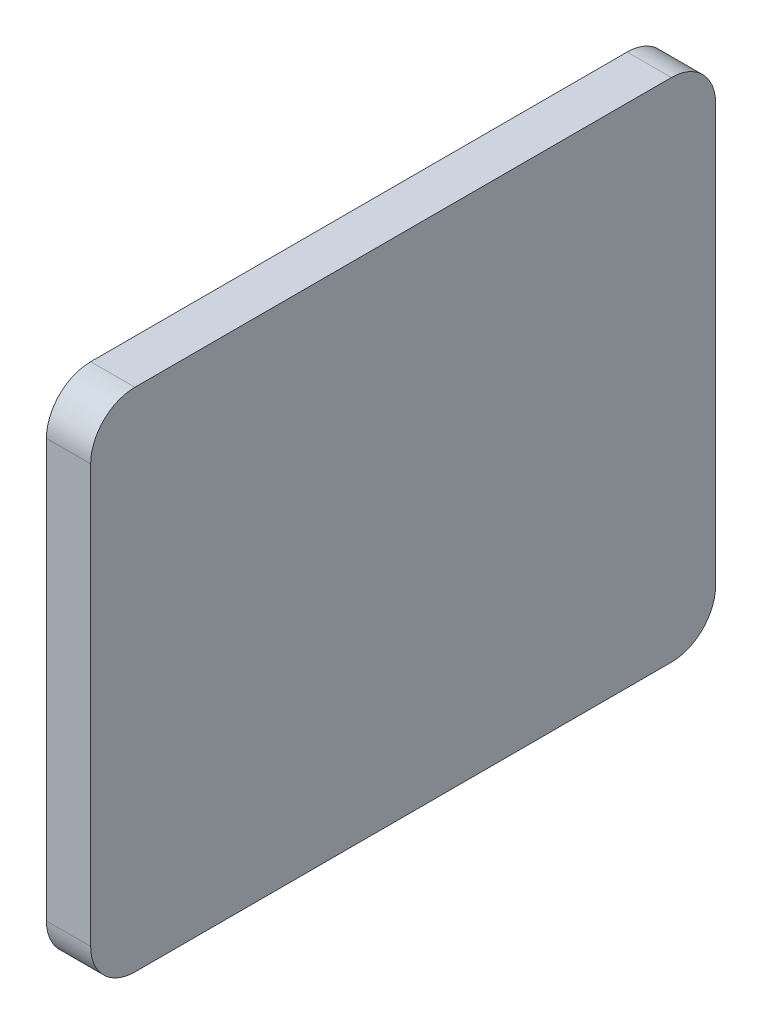
SolidWorks part; units mm, degrees
ref_plane "Front Plane" through (0, 0, 0) normal (0, 0, 1) x (1, 0, 0)
ref_plane "Top Plane" through (0, 0, 0) normal (0, 1, 0) x (1, 0, 0)
ref_plane "Right Plane" through (0, 0, 0) normal (1, 0, 0) x (0, 0, -1)
sketch "Sketch1" plane through (0, 0, 0) normal (1, 0, 0) x (0, 0, -1)
  line L1 (10, 0) -> (131.2922, 0)
  line L2 (0, -10) -> (0, -104.4885)
  line L3 (10, -114.4885) -> (131.2922, -114.4885)
  line L4 (141.2922, -10) -> (141.2922, -104.4885)
  arc A0 (131.2922, -114.4885) -> (141.2922, -104.4885) centre (131.2922, -104.4885) ccw
  arc A1 (10, -114.4885) -> (0, -104.4885) centre (10, -104.4885) cw
  arc A2 (10, 0) -> (0, -10) centre (10, -10) ccw
  arc A3 (131.2922, 0) -> (141.2922, -10) centre (131.2922, -10) cw
  dimension "D1" = 10
extrude "Boss-Extrude1" add sketch "Sketch1" along normal blind 10
sketch "Sketch2" plane through (0, 0, 0) normal (-1, 0, 0) x (0, 0, 1)
  line L1 (-136.0175, -87.5845) -> (-9.7778, -87.5845)
  line L2 (-136.0175, -87.5845) -> (-136.0175, -111.4358)
  line L3 (-136.0175, -111.4358) -> (-9.7778, -111.4358)
  line L4 (-9.7778, -87.5845) -> (-9.7778, -111.4358)
extrude "Boss-Extrude2" add sketch "Sketch2" along normal blind 1
sketch "Sketch3" plane through (0, 0, 0) normal (-1, 0, 0) x (0, 0, 1)
  line L1 (-95.1413, -8.4587) -> (-8.5205, -8.4587)
  line L2 (-95.1413, -8.4587) -> (-95.1413, -48.9396)
  line L3 (-95.1413, -48.9396) -> (-8.5205, -48.9396)
  line L4 (-8.5205, -8.4587) -> (-8.5205, -48.9396)
extrude "Cut-Extrude1" cut sketch "Sketch3" against normal blind 1
sketch "Sketch4" plane through (0, 0, 0) normal (-1, 0, 0) x (0, 0, 1)
  line L0 (-132.2131, -20.3589) -> (-128.7909, -24.9156)
  line L1 (-130.3672, -18.5747) -> (-126.8497, -22.8146)
  line L2 (-111.9319, -17.5151) -> (-115.0498, -22.1795)
  line L3 (-113.3237, -23.5919) -> (-110.5158, -18.6927)
  line L4 (-127.5897, -37.7547) -> (-130.5551, -42.5028)
  line L5 (-112.7792, -37.0375) -> (-109.3332, -41.4401)
  line L6 (-126.2203, -38.8907) -> (-129.2823, -43.4715)
  line L7 (-114.0146, -38.2855) -> (-110.5158, -42.5028)
  line L8 (-110.5158, -42.5028) -> (-110.4969, -42.5252)
  arc A0 (-132.2131, -20.3589) -> (-130.5551, -42.5028) centre (-120.5127, -30.6169) ccw
  arc A1 (-128.7909, -24.9156) -> (-127.5897, -37.7547) centre (-120.5127, -30.6169) ccw
  arc A2 (-115.0498, -22.1795) -> (-126.8497, -22.8146) centre (-120.5127, -30.6169) ccw
  arc A3 (-111.9882, -17.5993) -> (-130.3672, -18.5747) centre (-120.5127, -30.6169) ccw
  arc A4 (-126.2203, -38.8907) -> (-114.0146, -38.2855) centre (-120.5127, -30.6169) ccw
  arc A5 (-129.2819, -43.4709) -> (-110.4969, -42.5252) centre (-120.5127, -30.6169) ccw
  arc A6 (-112.7792, -37.0375) -> (-113.3237, -23.5919) centre (-120.5127, -30.6169) ccw
  arc A7 (-109.3332, -41.4401) -> (-110.5158, -18.6927) centre (-120.5127, -30.6169) ccw
  point P2 (-127.4859, -37.5886)
  point P11 (-112.7792, -37.0375)
extrude "Boss-Extrude3" add sketch "Sketch4" along normal blind 1 contours A1 L0 A0 L4 | L2 A3 L1 A2 | L5 A7 L3 A6 | L6 A5 L8 L7 A4
sketch "Sketch5" plane through (-1, 0, 0) normal (-1, 0, 0) x (0, 0, 1)
  line L0 (-122.6573, -19.3449) -> (-119.2891, -19.3449)
  line L1 (-119.2891, -19.3449) -> (-120.9732, -16.1746)
  line L2 (-120.9732, -16.1746) -> (-122.6573, -19.3449)
extrude "Cut-Extrude2" cut sketch "Sketch5" against normal blind 1
sketch "Sketch6" plane through (-1, 0, 0) normal (-1, 0, 0) x (0, 0, 1)
  line L0 (-132.0461, -29.687) -> (-132.0461, -33.1027)
  line L1 (-132.0461, -33.1027) -> (-135.4492, -31.3949)
  line L2 (-135.4492, -31.3949) -> (-132.0461, -29.687)
  line L3 (-122.5724, -41.7347) -> (-118.4594, -41.7347)
  line L4 (-118.4594, -41.7347) -> (-120.5159, -44.7663)
  line L5 (-120.5159, -44.7663) -> (-122.5724, -41.7347)
  line L6 (-109.6773, -28.718) -> (-109.6773, -32.698)
  line L7 (-109.6773, -32.698) -> (-106.1102, -30.2783)
  line L8 (-106.1102, -30.2783) -> (-109.6773, -28.718)
extrude "Cut-Extrude3" cut sketch "Sketch6" against normal blind 1
sketch "Sketch7" plane through (0, 0, 0) normal (-1, 0, 0) x (0, 0, 1)
  circle A0 centre (-120.7611, -31.1405) radius 5.8184
  point P2 (-120.7611, -31.1405)
extrude "Boss-Extrude4" add sketch "Sketch7" along normal blind 1
sketch "Sketch8" plane through (-1, 0, 0) normal (-1, 0, 0) x (0, 0, 1)
  line L0 (-121.1763, -28.9978) -> (-120.4435, -28.9978)
  line L1 (-120.4435, -28.9978) -> (-120.4435, -33.4647)
  line L2 (-121.1763, -28.9978) -> (-121.1744, -33.4887)
  line L3 (-121.924, -30.2154) -> (-121.682, -30.8856)
  line L4 (-119.7858, -30.2154) -> (-119.9704, -30.9276)
  arc A0 (-121.924, -30.2154) -> (-119.7858, -30.2154) centre (-120.8549, -32.0753) ccw
  arc A1 (-121.682, -30.8856) -> (-121.1744, -33.4887) centre (-120.8549, -32.0753) ccw
  arc A2 (-120.4435, -33.4647) -> (-119.9704, -30.9276) centre (-120.8549, -32.0753) ccw
  point P1 (-121.3518, -33.4365)
extrude "Cut-Extrude4" cut sketch "Sketch8" against normal blind 1
sketch "Sketch9" plane through (1, 0, 0) normal (-1, 0, 0) x (0, 0, 1)
  line L1 (-93.278, -10.5043) -> (-10.3118, -10.5043)
  line L2 (-93.278, -10.5043) -> (-93.278, -47.1944)
  line L3 (-93.278, -47.1944) -> (-10.3118, -47.1944)
  line L4 (-10.3118, -10.5043) -> (-10.3118, -47.1944)
extrude "Boss-Extrude5" add sketch "Sketch9" along normal blind 1
sketch "Sketch10" plane through (0, 0, 0) normal (-1, 0, 0) x (0, 0, 1)
  circle A0 centre (-85.8196, -69.1459) radius 6.4003
  circle A1 centre (-60.8719, -69.1459) radius 6.2565
  circle A2 centre (-37.8784, -69.1459) radius 5.7929
  point P4 (-37.8784, -69.1459)
extrude "Boss-Extrude6" add sketch "Sketch10" along normal blind 1
sketch "Sketch11" plane through (0, 0, 0) normal (-1, 0, 0) x (0, 0, 1)
  line L0 (-124.9995, -56.7638) -> (-122.0267, -56.7638)
  line L1 (-132.2152, -55.2914) -> (-98.6974, -55.2914)
  line L2 (-132.2152, -55.2914) -> (-132.2152, -84.0286)
  line L3 (-132.2152, -84.0286) -> (-98.6974, -84.0286)
  line L4 (-98.6974, -55.2914) -> (-98.6974, -84.0286)
  line L5 (-130.6033, -56.6632) -> (-127.6305, -56.6632)
  line L6 (-130.6033, -56.6632) -> (-130.6033, -58.7612)
  line L7 (-130.6033, -58.7612) -> (-127.6305, -58.7612)
  line L8 (-127.6305, -56.6632) -> (-127.6305, -58.7612)
  line L9 (-124.9995, -56.7638) -> (-124.9995, -58.8618)
  line L10 (-124.9995, -58.8618) -> (-122.0267, -58.8618)
  line L11 (-122.0267, -56.7638) -> (-122.0267, -58.8618)
  line L12 (-1.4864, -56.7638) -> (1.4864, -56.7638)
  line L13 (-1.4864, -56.7638) -> (-1.4864, -58.8618)
  line L14 (-1.4864, -58.8618) -> (1.4864, -58.8618)
  line L15 (1.4864, -56.7638) -> (1.4864, -58.8618)
  line L16 (-1.4864, -56.7638) -> (1.4864, -56.7638)
  line L17 (-1.4864, -56.7638) -> (-1.4864, -58.8618)
  line L18 (-1.4864, -58.8618) -> (1.4864, -58.8618)
  line L19 (1.4864, -56.7638) -> (1.4864, -58.8618)
  line L21 (-119.5759, -56.7638) -> (-116.4441, -56.7638)
  line L22 (-119.5759, -56.7638) -> (-119.5759, -58.8859)
  line L23 (-119.5759, -58.8859) -> (-116.4441, -58.8859)
  line L24 (-116.4441, -56.7638) -> (-116.4441, -58.8859)
  line L25 (-114.2123, -56.7638) -> (-111.2408, -56.7638)
  line L26 (-114.2123, -56.7638) -> (-114.2123, -59.0052)
  line L27 (-114.2123, -59.0052) -> (-111.2408, -59.0052)
  line L28 (-111.2408, -56.7638) -> (-111.2408, -59.0052)
  line L29 (-108.5727, -56.7638) -> (-105.7946, -56.7638)
  line L30 (-108.5727, -56.7638) -> (-108.5727, -59.0052)
  line L31 (-108.5727, -59.0052) -> (-105.7946, -59.0052)
  line L32 (-105.7946, -56.7638) -> (-105.7946, -59.0052)
  line L33 (-103.3284, -56.7638) -> (-100.4528, -56.7638)
  line L34 (-103.3284, -56.7638) -> (-103.3284, -59.0052)
  line L35 (-103.3284, -59.0052) -> (-100.4528, -59.0052)
  line L36 (-100.4528, -56.7638) -> (-100.4528, -59.0052)
  line L37 (-130.7125, -60.9213) -> (-127.6305, -60.9213)
  line L38 (-130.7125, -60.9213) -> (-130.7125, -63.1632)
  line L39 (-130.7125, -63.1632) -> (-127.6305, -63.1632)
  line L40 (-127.6305, -60.9213) -> (-127.6305, -63.1632)
  line L41 (-130.7125, -65.4686) -> (-127.6305, -65.4686)
  line L42 (-130.7125, -65.4686) -> (-130.7125, -67.9428)
  line L43 (-130.7125, -67.9428) -> (-127.6305, -67.9428)
  line L44 (-127.6305, -65.4686) -> (-127.6305, -67.9428)
  line L45 (-130.7125, -70.4302) -> (-127.6305, -70.4302)
  line L46 (-130.7125, -70.4302) -> (-130.7125, -72.9487)
  line L47 (-130.7125, -72.9487) -> (-127.6305, -72.9487)
  line L48 (-127.6305, -70.4302) -> (-127.6305, -72.9487)
  line L49 (-130.7125, -75.6103) -> (-127.6305, -75.6103)
  line L50 (-130.7125, -75.6103) -> (-130.7125, -77.9537)
  line L51 (-130.7125, -77.9537) -> (-127.6305, -77.9537)
  line L52 (-127.6305, -75.6103) -> (-127.6305, -77.9537)
  line L53 (-130.7125, -79.3964) -> (-127.6305, -79.3964)
  line L54 (-130.7125, -79.3964) -> (-130.7125, -81.9145)
  line L55 (-130.7125, -81.9145) -> (-127.6305, -81.9145)
  line L56 (-127.6305, -79.3964) -> (-127.6305, -81.9145)
  line L57 (-124.9995, -60.9213) -> (-122.0267, -60.9213)
  line L58 (-124.9995, -60.9213) -> (-124.9995, -63.1632)
  line L59 (-124.9995, -63.1632) -> (-122.0267, -63.1632)
  line L60 (-122.0267, -60.9213) -> (-122.0267, -63.1632)
  line L61 (-124.9995, -65.4686) -> (-122.0267, -65.4686)
  line L62 (-124.9995, -65.4686) -> (-124.9995, -67.9428)
  line L63 (-124.9995, -67.9428) -> (-122.0267, -67.9428)
  line L64 (-122.0267, -65.4686) -> (-122.0267, -67.9428)
  line L65 (-124.9995, -70.4302) -> (-122.0267, -70.4302)
  line L66 (-124.9995, -70.4302) -> (-124.9995, -72.9487)
  line L67 (-124.9995, -72.9487) -> (-122.0267, -72.9487)
  line L68 (-122.0267, -70.4302) -> (-122.0267, -72.9487)
  line L69 (-124.9995, -75.6103) -> (-122.0267, -75.6103)
  line L70 (-124.9995, -75.6103) -> (-124.9995, -77.9537)
  line L71 (-124.9995, -77.9537) -> (-122.0267, -77.9537)
  line L72 (-122.0267, -75.6103) -> (-122.0267, -77.9537)
  line L73 (-124.9995, -79.3964) -> (-122.0267, -79.3964)
  line L74 (-124.9995, -79.3964) -> (-124.9995, -81.9145)
  line L75 (-124.9995, -81.9145) -> (-122.0267, -81.9145)
  line L76 (-122.0267, -79.3964) -> (-122.0267, -81.9145)
  line L77 (-119.5759, -60.9213) -> (-116.4441, -60.9213)
  line L78 (-119.5759, -60.9213) -> (-119.5759, -63.1632)
  line L79 (-119.5759, -63.1632) -> (-116.4441, -63.1632)
  line L80 (-116.4441, -60.9213) -> (-116.4441, -63.1632)
  line L81 (-114.2123, -60.9213) -> (-111.2408, -60.9213)
  line L82 (-114.2123, -60.9213) -> (-114.2123, -63.1632)
  line L83 (-114.2123, -63.1632) -> (-111.2408, -63.1632)
  line L84 (-111.2408, -60.9213) -> (-111.2408, -63.1632)
  line L85 (-108.5727, -60.9213) -> (-105.7946, -60.9213)
  line L86 (-108.5727, -60.9213) -> (-108.5727, -63.1632)
  line L87 (-108.5727, -63.1632) -> (-105.7946, -63.1632)
  line L88 (-105.7946, -60.9213) -> (-105.7946, -63.1632)
  line L89 (-103.3284, -60.9213) -> (-100.4528, -60.9213)
  line L90 (-103.3284, -60.9213) -> (-103.3284, -63.1632)
  line L91 (-103.3284, -63.1632) -> (-100.4528, -63.1632)
  line L92 (-100.4528, -60.9213) -> (-100.4528, -63.1632)
  line L93 (-119.5759, -65.4686) -> (-116.1815, -65.4686)
  line L94 (-119.5759, -65.4686) -> (-119.5759, -67.9428)
  line L95 (-119.5759, -67.9428) -> (-116.1815, -67.9428)
  line L96 (-116.1815, -65.4686) -> (-116.1815, -67.9428)
  line L97 (-114.2123, -65.4686) -> (-111.2408, -65.4686)
  line L98 (-114.2123, -65.4686) -> (-114.2123, -67.9428)
  line L99 (-114.2123, -67.9428) -> (-111.2408, -67.9428)
  line L100 (-111.2408, -65.4686) -> (-111.2408, -67.9428)
  line L101 (-108.5727, -65.4686) -> (-105.7946, -65.4686)
  line L102 (-108.5727, -65.4686) -> (-108.5727, -67.9428)
  line L103 (-108.5727, -67.9428) -> (-105.7946, -67.9428)
  line L104 (-105.7946, -65.4686) -> (-105.7946, -67.9428)
  line L105 (-103.3284, -65.4686) -> (-100.4528, -65.4686)
  line L106 (-103.3284, -65.4686) -> (-103.3284, -67.9428)
  line L107 (-103.3284, -67.9428) -> (-100.4528, -67.9428)
  line L108 (-100.4528, -65.4686) -> (-100.4528, -67.9428)
  line L109 (-119.5759, -70.4302) -> (-116.4441, -70.4302)
  line L110 (-119.5759, -70.4302) -> (-119.5759, -72.9487)
  line L111 (-119.5759, -72.9487) -> (-116.4441, -72.9487)
  line L112 (-116.4441, -70.4302) -> (-116.4441, -72.9487)
  line L113 (-114.2123, -70.4302) -> (-111.2408, -70.4302)
  line L114 (-114.2123, -70.4302) -> (-114.2123, -72.9487)
  line L115 (-114.2123, -72.9487) -> (-111.2408, -72.9487)
  line L116 (-111.2408, -70.4302) -> (-111.2408, -72.9487)
  line L117 (-108.5727, -70.4302) -> (-105.7946, -70.4302)
  line L118 (-108.5727, -70.4302) -> (-108.5727, -72.9487)
  line L119 (-108.5727, -72.9487) -> (-105.7946, -72.9487)
  line L120 (-105.7946, -70.4302) -> (-105.7946, -72.9487)
  line L121 (-103.3284, -70.4302) -> (-100.4528, -70.4302)
  line L122 (-103.3284, -70.4302) -> (-103.3284, -72.9487)
  line L123 (-103.3284, -72.9487) -> (-100.4528, -72.9487)
  line L124 (-100.4528, -70.4302) -> (-100.4528, -72.9487)
  line L125 (-119.5759, -75.6103) -> (-116.4441, -75.6103)
  line L126 (-119.5759, -75.6103) -> (-119.5759, -77.9537)
  line L127 (-119.5759, -77.9537) -> (-116.4441, -77.9537)
  line L128 (-116.4441, -75.6103) -> (-116.4441, -77.9537)
  line L129 (-114.2123, -75.4941) -> (-111.2408, -75.4941)
  line L130 (-114.2123, -75.4941) -> (-114.2123, -77.9537)
  line L131 (-114.2123, -77.9537) -> (-111.2408, -77.9537)
  line L132 (-111.2408, -75.4941) -> (-111.2408, -77.9537)
  line L133 (-108.5727, -75.4941) -> (-105.7946, -75.4941)
  line L134 (-108.5727, -75.4941) -> (-108.5727, -77.9537)
  line L135 (-108.5727, -77.9537) -> (-105.7946, -77.9537)
  line L136 (-105.7946, -75.4941) -> (-105.7946, -77.9537)
  line L137 (-103.3284, -75.4941) -> (-100.4528, -75.4941)
  line L138 (-103.3284, -75.4941) -> (-103.3284, -77.9537)
  line L139 (-103.3284, -77.9537) -> (-100.4528, -77.9537)
  line L140 (-100.4528, -75.4941) -> (-100.4528, -77.9537)
  line L141 (-119.5759, -79.3964) -> (-116.4441, -79.3964)
  line L142 (-119.5759, -79.3964) -> (-119.5759, -81.9145)
  line L143 (-119.5759, -81.9145) -> (-116.4441, -81.9145)
  line L144 (-116.4441, -79.3964) -> (-116.4441, -81.9145)
  line L145 (-114.2123, -79.3964) -> (-111.2408, -79.3964)
  line L146 (-114.2123, -79.3964) -> (-114.2123, -82.0606)
  line L147 (-114.2123, -82.0606) -> (-111.2408, -82.0606)
  line L148 (-111.2408, -79.3964) -> (-111.2408, -82.0606)
  line L149 (-108.5727, -79.3964) -> (-105.7946, -79.3964)
  line L150 (-108.5727, -79.3964) -> (-108.5727, -82.0606)
  line L151 (-108.5727, -82.0606) -> (-105.7946, -82.0606)
  line L152 (-105.7946, -79.3964) -> (-105.7946, -82.0606)
  line L153 (-103.3284, -79.3964) -> (-100.4528, -79.3964)
  line L154 (-103.3284, -79.3964) -> (-103.3284, -82.0606)
  line L155 (-103.3284, -82.0606) -> (-100.4528, -82.0606)
  line L156 (-100.4528, -79.3964) -> (-100.4528, -82.0606)
extrude "Boss-Extrude8" add sketch "Sketch11" along normal blind 1 contours L8 L5 L6 L7 | L40 L37 L38 L39 | L44 L41 L42 L43 | L48 L45 L46 L47 | L52 L49 L50 L51 | L76 L73 L74 L75 | L72 L69 L70 L71 | L68 L65 L66 L67 | L64 L61 L62 L63 | L60 L57 L58 L59 | L11 L0 L9 L10 | L24 L21 L22 L23 | L80 L77 L78 L79 | L96 L93 L94 L95 | L112 L109 L110 L111 | L128 L125 L126 L127 | L144 L141 L142 L143 | L148 L145 L146 L147 | L132 L129 L130 L131 | L116 L113 L114 L115 | L84 L81 L82 L83 | L28 L25 L26 L27 | L32 L29 L30 L31 | L88 L85 L86 L87 | L104 L101 L102 L103 | L120 L117 L118 L119 | L136 L133 L134 L135 | L152 L149 L150 L151 | L156 L153 L154 L155 | L140 L137 L138 L139 | L124 L121 L122 L123 | L108 L105 L106 L107 | L92 L89 L90 L91 | L36 L33 L34 L35 | L56 L55 L54 L53 | L97 L100 L99 L98
sketch "Sketch12" plane through (0, 0, 0) normal (-1, 0, 0) x (0, 0, 1)
  line L1 (-133.2407, -54.6964) -> (-97.6755, -54.6964)
  line L2 (-133.2407, -54.6964) -> (-133.2407, -84.366)
  line L3 (-133.2407, -84.366) -> (-97.6755, -84.366)
  line L4 (-97.6755, -54.6964) -> (-97.6755, -84.366)
  line L5 (-132.4303, -55.3589) -> (-98.6763, -55.3589)
  line L6 (-132.4303, -55.3589) -> (-132.4303, -83.6565)
  line L7 (-132.4303, -83.6565) -> (-98.6763, -83.6565)
  line L8 (-98.6763, -55.3589) -> (-98.6763, -83.6565)
extrude "Boss-Extrude9" add sketch "Sketch12" along normal blind 1
sketch "Sketch13" plane through (0, 0, 0) normal (-1, 0, 0) x (0, 0, 1)
  line L1 (-91.0194, -12.7672) -> (-80.505, -12.7672)
  line L2 (-91.0194, -12.7672) -> (-91.0194, -17.7701)
  line L3 (-91.0194, -17.7701) -> (-80.505, -17.7701)
  line L4 (-80.505, -12.7672) -> (-80.505, -17.7701)
  line L5 (-80.505, -14.2408) -> (-79.5475, -14.2408)
  line L6 (-80.505, -14.2408) -> (-80.505, -16.1953)
  line L7 (-80.505, -16.1953) -> (-79.5475, -16.1953)
  line L8 (-79.5475, -14.2408) -> (-79.5475, -16.1953)
extrude "Cut-Extrude5" cut sketch "Sketch13" against normal blind 1 contours L4 L1 L2 L3 | L8 L5 L4 L7
sketch "Sketch14" plane through (1, 0, 0) normal (-1, 0, 0) x (0, 0, 1)
  line L1 (-90.3761, -13.2499) -> (-88.5898, -13.2499)
  line L2 (-90.3761, -13.2499) -> (-90.3761, -17.3688)
  line L3 (-90.3761, -17.3688) -> (-88.5898, -17.3688)
  line L4 (-88.5898, -13.2499) -> (-88.5898, -17.3688)
  line L5 (-87.6464, -13.2499) -> (-85.9931, -13.2499)
  line L6 (-87.6464, -13.2499) -> (-87.6464, -17.3688)
  line L7 (-87.6464, -17.3688) -> (-85.9931, -17.3688)
  line L8 (-85.9931, -13.2499) -> (-85.9931, -17.3688)
  line L9 (-85.3146, -13.2499) -> (-83.7932, -13.2499)
  line L10 (-85.3146, -13.2499) -> (-85.3146, -17.3688)
  line L11 (-85.3146, -17.3688) -> (-83.7932, -17.3688)
  line L12 (-83.7932, -13.2499) -> (-83.7932, -17.3688)
  line L13 (-82.8766, -13.2499) -> (-81.4087, -13.2499)
  line L14 (-82.8766, -13.2499) -> (-82.8766, -17.3688)
  line L15 (-82.8766, -17.3688) -> (-81.4087, -17.3688)
  line L16 (-81.4087, -13.2499) -> (-81.4087, -17.3688)
extrude "Boss-Extrude10" add sketch "Sketch14" along normal blind 1
sketch "Sketch15" plane through (0, 0, 0) normal (-1, 0, 0) x (0, 0, 1)
  line L1 (-76.0669, -12.5916) -> (-74.4007, -12.5916)
  line L2 (-76.0669, -12.5916) -> (-76.0669, -18.1366)
  line L3 (-76.0669, -18.1366) -> (-74.4007, -18.1366)
  line L4 (-74.4007, -12.5916) -> (-74.4007, -18.1366)
  line L5 (-73.4129, -13.583) -> (-71.9662, -13.583)
  line L6 (-73.4129, -13.583) -> (-73.4129, -18.1366)
  line L7 (-73.4129, -18.1366) -> (-71.9662, -18.1366)
  line L8 (-71.9662, -13.583) -> (-71.9662, -18.1366)
  line L9 (-70.6716, -14.7042) -> (-69.3584, -14.7042)
  line L10 (-70.6716, -14.7042) -> (-70.6716, -18.1366)
  line L11 (-70.6716, -18.1366) -> (-69.3584, -18.1366)
  line L12 (-69.3584, -14.7042) -> (-69.3584, -18.1366)
  line L13 (-68.2573, -16.4204) -> (-67.2055, -16.4204)
  line L14 (-68.2573, -16.4204) -> (-68.2573, -18.1366)
  line L15 (-68.2573, -18.1366) -> (-67.2055, -18.1366)
  line L16 (-67.2055, -16.4204) -> (-67.2055, -18.1366)
extrude "Cut-Extrude6" cut sketch "Sketch15" against normal blind 1
sketch "Sketch16" plane through (0, 0, 0) normal (-1, 0, 0) x (0, 0, 1)
  line L0 (-14.8645, -12.523) -> (-14.8624, -15.8632)
  line L1 (-14.8593, -20.9513) -> (-11.7247, -18.5879)
  line L2 (-11.7247, -18.5879) -> (-14.0372, -16.6134)
  line L3 (-14.0372, -16.6134) -> (-11.8887, -14.7369)
  line L4 (-11.8887, -14.7369) -> (-14.8645, -12.523)
  line L5 (-14.2979, -13.673) -> (-14.2979, -15.904)
  line L6 (-14.2979, -15.904) -> (-12.8296, -14.7885)
  line L7 (-12.8296, -14.7885) -> (-14.2979, -13.673)
  line L8 (-14.3785, -17.4582) -> (-14.3785, -19.8185)
  line L9 (-14.3785, -19.8185) -> (-12.7582, -18.5879)
  line L10 (-12.7582, -18.5879) -> (-14.3785, -17.4582)
  line L12 (-17.2701, -15.2088) -> (-17.1626, -14.2695)
  line L13 (-17.1626, -14.2695) -> (-14.8624, -15.8632)
  line L14 (-14.8613, -17.6284) -> (-14.8593, -20.9513)
  line L15 (-17.0231, -18.8317) -> (-17.2655, -17.8976)
  line L16 (-17.2655, -17.8976) -> (-15.012, -16.6805)
  line L17 (-14.8613, -17.6284) -> (-17.0231, -18.8317)
  line L18 (-15.012, -16.6805) -> (-17.2701, -15.2088)
  point P10 (-11.987, -16.33)
  point P16 (-12.2345, -15.2959)
  point P17 (-11.9983, -16.2062)
  point P18 (-11.8274, -14.358)
  point P19 (-11.7247, -18.5879)
  point P21 (-13.0793, -14.9782)
  point P22 (-11.902, -14.9782)
  point P23 (-12.99, -18.5318)
  point P24 (-11.8274, -18.646)
  point P25 (-12.757, -16.5241)
  point P26 (-13.4492, -16.8423)
  point P27 (-15.0647, -16.709)
  point P30 (-14.8645, -12.523)
  point P31 (-14.8937, -20.6771)
  point P32 (-14.3785, -19.6887)
  point P33 (-14.0372, -16.6134)
  point P34 (-11.8887, -14.7369)
  point P35 (-12.7582, -18.5879)
  point P36 (-14.3785, -19.8185)
  point P37 (-11.5596, -18.5879)
  point P38 (-14.8613, -20.9513)
extrude "Boss-Extrude12" add sketch "Sketch16" along normal blind 1
sketch "Sketch17" plane through (0, 0, 0) normal (-1, 0, 0) x (0, 0, 1)
  line L1 (-92.3422, -42.1313) -> (-11.7846, -42.1313)
  line L2 (-92.3422, -42.1313) -> (-92.3422, -47.03)
  line L3 (-92.3422, -47.03) -> (-11.7846, -47.03)
  line L4 (-11.7846, -42.1313) -> (-11.7846, -47.03)
extrude "Boss-Extrude13" add sketch "Sketch17" along normal blind 1
sketch "Sketch18" plane through (-1, 0, 0) normal (-1, 0, 0) x (0, 0, 1)
  line L0 (-55.6384, -46.6052) -> (-50.9604, -46.6052)
  line L1 (-55.6384, -46.6052) -> (-53.2994, -43.389)
  line L2 (-53.2994, -43.389) -> (-50.9604, -46.6052)
extrude "Cut-Extrude7" cut sketch "Sketch18" against normal blind 1
sketch "Sketch22" plane through (0, 0, 0) normal (-1, 0, 0) x (0, 0, 1)
  line L0 (-80.4592, -28.2327) -> (-79.9749, -28.8952)
  line L1 (-48.2038, -21.3268) -> (-47.6765, -21.7946)
  spline S0 degree 3 poles (-80.4592, -28.2327) (-76.2684, -11.0292) (-74.745, -37.5204) (-70.1351, -26.2764) (-67.2776, -19.5265) (-64.6874, -26.0622) (-64.1694, -32.696) (-59.6029, -26.3026) (-57.9661, -18.9305) (-53.9163, -25.3332) (-52.4968, -33.732) (-47.3627, -22.4043) (-48.2038, -21.3268) knots 0 0 0 0 0.245441 0.321752 0.400898 0.480363 0.541013 0.625945 0.7062 0.797593 0.853509 1 1 1 1
  spline S1 degree 3 poles (-79.9749, -28.8952) (-76.2351, -14.3697) (-74.7638, -38.7814) (-70.3411, -27.8513) (-67.4857, -21.1304) (-64.895, -27.6586) (-64.3768, -34.2938) (-59.8116, -27.901) (-58.1699, -20.5249) (-54.1376, -26.9424) (-52.5589, -35.833) (-46.9247, -22.0099) (-47.6765, -21.7946) knots 0 0 0 0 0.227694 0.303865 0.382865 0.462184 0.522723 0.607499 0.687606 0.778831 0.834645 1 1 1 1
extrude "Boss-Extrude14" add sketch "Sketch22" along normal blind 1
